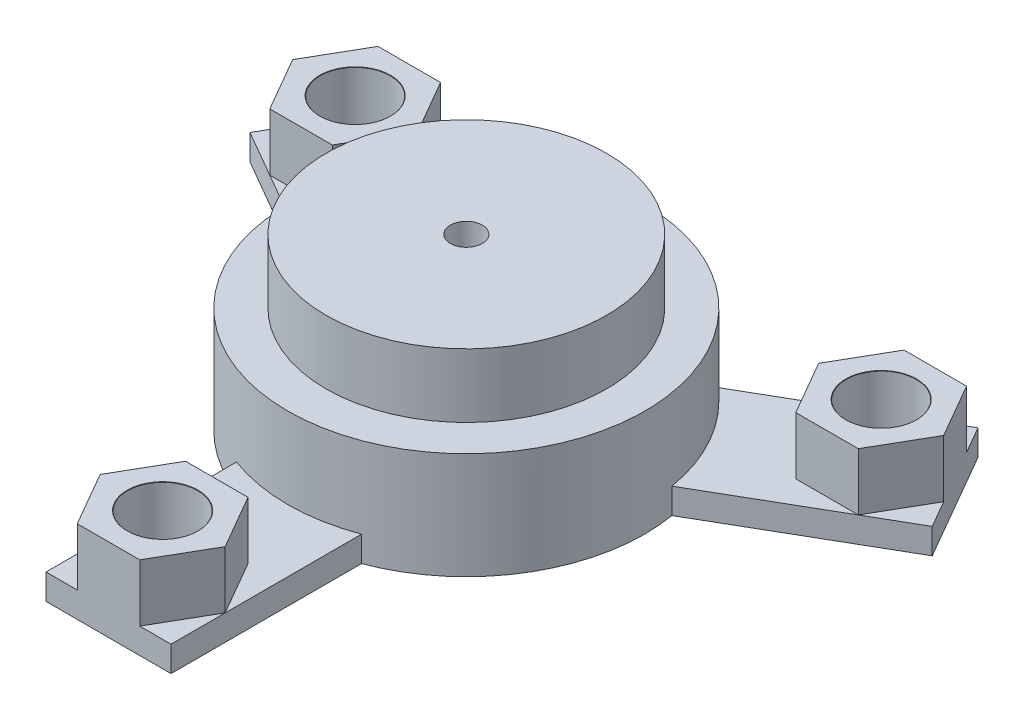
SolidWorks part; units mm, degrees
ref_plane "Plan de face" through (0, 0, 0) normal (0, 0, 1) x (1, 0, 0)
ref_plane "Plan de dessus" through (0, 0, 0) normal (0, 1, 0) x (1, 0, 0)
ref_plane "Plan de droite" through (0, 0, 0) normal (1, 0, 0) x (0, 0, -1)
sketch "Esquisse1" plane through (0, 0, 0) normal (0, 1, 0) x (1, 0, 0)
  circle A0 centre (0, 0) radius 11
  dimension "D1" = 22
extrude "Boss.-Extru.1" add sketch "Esquisse1" along normal blind 5
sketch "Esquisse2" plane through (0, 5, 0) normal (0, 1, 0) x (1, 0, 0)
  circle A0 centre (0, 0) radius 9
  dimension "D1" = 18
extrude "Boss.-Extru.2" [suppressed] add sketch "Esquisse2" along normal blind 8
sketch "Esquisse3" plane through (0, 0, 0) normal (0, -1, 0) x (1, 0, 0)
  circle A0 centre (0, 0) radius 14
  dimension "D1" = 28
extrude "Boss.-Extru.3" add sketch "Esquisse3" along normal blind 8.35
sketch "Esquisse4" plane through (0, -8.35, 0) normal (0, -1, 0) x (1, 0, 0)
  line L2 (1.775, -2.0345) -> (1.775, 2.0345)
  line L4 (-1.775, -2.0345) -> (-1.775, 2.0345)
  line L5 (1.775, -2.7) -> (-1.775, 2.7) construction
  line L6 (1.775, 2.7) -> (-1.775, -2.7) construction
  arc A0 (1.775, 2.0345) -> (-1.775, 2.0345) centre (0, 0) ccw
  arc A1 (-1.775, -2.0345) -> (1.775, -2.0345) centre (0, 0) ccw
  circle A2 centre (0, 0) radius 7.5
  dimension "D1" = 5.4
  dimension "D6" = 15
  dimension "D2" = 3.55
  dimension "D3" = 5.4
  dimension "D4" = 4.0691
  dimension "D5" = 4.0691
extrude "Boss.-Extru.5" [suppressed] add sketch "Esquisse4" along normal blind 7
sketch "Esquisse5" plane through (0, -8.35, 0) normal (0, -1, 0) x (1, 0, 0)
  circle A0 centre (0, 0) radius 1.25
  dimension "D1" = 2.5
extrude "Enlèv. mat.-Extru.1" cut sketch "Esquisse5" against normal through all both and the other way through all
sketch "Esquisse6" [suppressed] plane through (0, 13, 0) normal (0, 1, 0) x (1, 0, 0)
  circle A0 centre (0, 0) radius 6.5
  dimension "D1" = 13
extrude "Enlèv. mat.-Extru.2" [suppressed] cut sketch "Esquisse6" against normal blind 13
sketch "Esquisse8" plane through (0, -8.35, 0) normal (0, -1, 0) x (1, 0, 0)
  line L1 (-4.9, 28.05) -> (4.9, 28.05)
  line L2 (-4.9, 28.05) -> (-4.9, 5.678)
  line L4 (4.9, 28.05) -> (4.9, 5.678)
  arc A0 (4.9, 5.678) -> (-4.9, 5.678) centre (0, 0) ccw
  dimension "D4" = 15
  dimension "D2" = 4.9
  dimension "D3" = 9.8
extrude "Boss.-Extru.6" add sketch "Esquisse8" against normal blind 2
pattern_circular "Répétition circulaire1" count 3 every 120 about axis through (0, 0, 0) along (0, 1, 0) of "Boss.-Extru.6"
sketch "Esquisse13" plane through (0, -6.35, 0) normal (0, 1, 0) x (1, 0, 0)
  line L0 (-26.742, 9.7815) -> (-21.842, 18.2685) construction
  line L1 (-23.067, 16.1468) -> (-25.517, 11.9032)
  line L2 (-25.517, 11.9032) -> (-23.067, 7.6597)
  line L3 (-23.067, 7.6597) -> (-18.167, 7.6597)
  line L4 (-18.167, 7.6597) -> (-15.717, 11.9032)
  line L5 (-15.717, 11.9032) -> (-18.167, 16.1468)
  line L6 (-18.167, 16.1468) -> (-23.067, 16.1468)
  line L7 (-13.8075, 2.3137) -> (-26.742, 9.7815) construction
  circle A0 centre (-20.617, 11.9032) radius 4.2435 construction
  dimension "D1" = 4.9
  dimension "D2" = 180
  dimension "D3" = 4.9
extrude "Boss.-Extru.8" add sketch "Esquisse13" along normal blind 4.5
pattern_circular "Répétition circulaire3" count 3 every 120 about axis through (0, 0, 0) along (0, 1, 0) of "Boss.-Extru.8"
hole_wizard "Dégagement M51" positions "Esquisse3D2" profile "Esquisse16" hole size "M5" standard "ISO" end condition through all
sketch3d "Esquisse3D2"
  point P0 (-20.617, -1.85, -11.9032)
  dimension "D1" = 4.9
  dimension "D2" = 4.9
sketch "Esquisse16" plane through (-20.617, -1.85, -11.9032) normal (1, 0, 0) x (0, 0, 1)
  line L0 (0, 0) -> (0, 6.5)
  line L1 (0, 6.5) -> (2.75, 6.5)
  line L2 (2.75, 6.5) -> (2.75, 0.025)
  line L3 (2.75, 0.025) -> (2.775, 0)
  line L5 (2.775, 0) -> (0, 0)
  line L6 (-2.75, 0.025) -> (-2.775, 0) construction
  line L11 (0, -6.35) -> (0, 107.95) construction
  dimension "Diamètre du perçage jusqu'au prochain" = 5.5
  dimension "Profondeur du perçage jusqu'au prochain" = 6.5
  dimension "Diamètre du fraisage entrant" = 5.55
  dimension "Angle du fraisage entrant" = 90
pattern_circular "Répétition circulaire4" count 3 every 120 about axis through (0, 0, 0) along (0, 1, 0) of "Dégagement M51"
